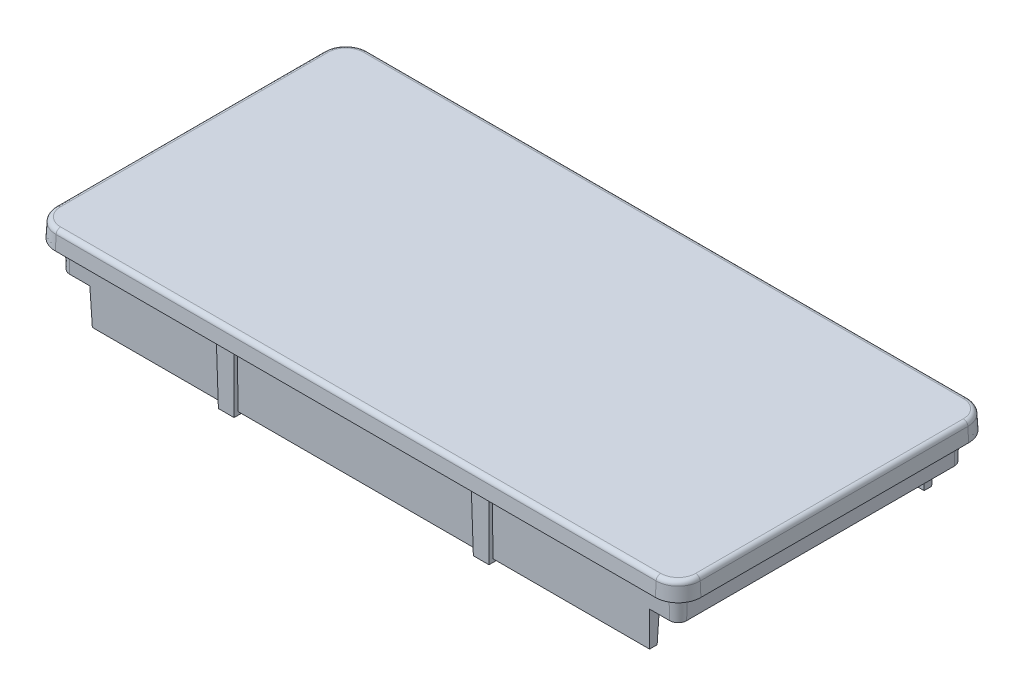
SolidWorks part; units mm, degrees
material "ABS PC"
ref_plane "Front" through (0, 0, 0) normal (0, 0, 1) x (1, 0, 0)
ref_plane "Top" through (0, 0, 0) normal (0, 1, 0) x (1, 0, 0)
ref_plane "Right" through (0, 0, 0) normal (1, 0, 0) x (0, 0, -1)
sketch "Sketch1" plane through (0, 0, 0) normal (0, 1, 0) x (1, 0, 0)
  line L1 (-32.95, -17.2) -> (32.95, -17.2)
  line L2 (-35.45, -14.7) -> (-35.45, 14.7)
  line L3 (-32.95, 17.2) -> (32.95, 17.2)
  line L4 (35.45, -14.7) -> (35.45, 14.7)
  line L5 (-35.45, -17.2) -> (35.45, 17.2) construction
  line L6 (-35.45, 17.2) -> (35.45, -17.2) construction
  arc A0 (32.95, -17.2) -> (35.45, -14.7) centre (32.95, -14.7) ccw
  arc A1 (-35.45, 14.7) -> (-32.95, 17.2) centre (-32.95, 14.7) cw
  arc A2 (-32.95, -17.2) -> (-35.45, -14.7) centre (-32.95, -14.7) cw
  arc A3 (32.95, 17.2) -> (35.45, 14.7) centre (32.95, 14.7) cw
  point P0 (0, 0)
  dimension "D3" = 2.5
  dimension "D1" = 70.9
  dimension "D2" = 34.4
extrude "Boss-Extrude1" add sketch "Sketch1" along normal blind 2 draft 3
fillet "Fillet1" radius 0.5 8 edges at (0, 2, 17.0952) (-34.6437, 2, 16.3937) (-35.3452, 2, 0) (-34.6437, 2, -16.3937) (0, 2, -17.0952) (34.6437, 2, -16.3937) (35.3452, 2, 0) (34.6437, 2, 16.3937)
sketch "Sketch2" plane through (0, 0, 0) normal (0, -1, 0) x (1, 0, 0)
  line L8 (32.95, 16.45) -> (-32.95, 16.45)
  line L9 (-34.7, 14.7) -> (-34.7, -14.7)
  line L10 (-32.95, -16.45) -> (32.95, -16.45)
  line L11 (34.7, -14.7) -> (34.7, 14.7)
  line L12 (32.95, 16.45) -> (-32.95, 16.45)
  line L13 (-34.7, 14.7) -> (-34.7, -14.7)
  line L14 (-32.95, -16.45) -> (32.95, -16.45)
  line L15 (34.7, -14.7) -> (34.7, 14.7)
  arc A8 (34.7, 14.7) -> (32.95, 16.45) centre (32.95, 14.7) ccw
  arc A9 (-32.95, 16.45) -> (-34.7, 14.7) centre (-32.95, 14.7) ccw
  arc A10 (-34.7, -14.7) -> (-32.95, -16.45) centre (-32.95, -14.7) ccw
  arc A11 (32.95, -16.45) -> (34.7, -14.7) centre (32.95, -14.7) ccw
  arc A12 (34.7, 14.7) -> (32.95, 16.45) centre (32.95, 14.7) ccw
  arc A13 (-32.95, 16.45) -> (-34.7, 14.7) centre (-32.95, 14.7) ccw
  arc A14 (-34.7, -14.7) -> (-32.95, -16.45) centre (-32.95, -14.7) ccw
  arc A15 (32.95, -16.45) -> (34.7, -14.7) centre (32.95, -14.7) ccw
  dimension "D1" = 0.75
extrude "Cut-Extrude1" cut sketch "Sketch2" against normal blind 0.5
sketch "Sketch4" plane through (0, 0.5, 0) normal (0, -1, 0) x (1, 0, 0)
  line L1 (31.65, -14.4) -> (-31.65, -14.4)
  line L2 (32.65, -13.4) -> (32.65, 13.4)
  line L3 (31.65, 14.4) -> (-31.65, 14.4)
  line L4 (-32.65, -13.4) -> (-32.65, 13.4)
  line L5 (32.65, -14.4) -> (-32.65, 14.4) construction
  line L6 (32.65, 14.4) -> (-32.65, -14.4) construction
  line L8 (32.95, 15.75) -> (-32.95, 15.75)
  line L9 (-34, 14.7) -> (-34, -14.7)
  line L10 (-32.95, -15.75) -> (32.95, -15.75)
  line L11 (34, -14.7) -> (34, 14.7)
  line L12 (32.95, 15.75) -> (-32.95, 15.75)
  line L13 (-34, 14.7) -> (-34, -14.7)
  line L14 (-32.95, -15.75) -> (32.95, -15.75)
  line L15 (34, -14.7) -> (34, 14.7)
  arc A0 (32.65, 13.4) -> (31.65, 14.4) centre (31.65, 13.4) ccw
  arc A1 (31.65, -14.4) -> (32.65, -13.4) centre (31.65, -13.4) ccw
  arc A2 (-31.65, -14.4) -> (-32.65, -13.4) centre (-31.65, -13.4) cw
  arc A3 (-31.65, 14.4) -> (-32.65, 13.4) centre (-31.65, 13.4) ccw
  arc A8 (34, 14.7) -> (32.95, 15.75) centre (32.95, 14.7) ccw
  arc A9 (-32.95, 15.75) -> (-34, 14.7) centre (-32.95, 14.7) ccw
  arc A10 (-34, -14.7) -> (-32.95, -15.75) centre (-32.95, -14.7) ccw
  arc A11 (32.95, -15.75) -> (34, -14.7) centre (32.95, -14.7) ccw
  arc A12 (34, 14.7) -> (32.95, 15.75) centre (32.95, 14.7) ccw
  arc A13 (-32.95, 15.75) -> (-34, 14.7) centre (-32.95, 14.7) ccw
  arc A14 (-34, -14.7) -> (-32.95, -15.75) centre (-32.95, -14.7) ccw
  arc A15 (32.95, -15.75) -> (34, -14.7) centre (32.95, -14.7) ccw
  point P0 (0, 0)
  dimension "D4" = 1
  dimension "D2" = 1.35
  dimension "D3" = 1.35
  dimension "D1" = 0.7
extrude "Boss-Extrude2" add sketch "Sketch4" along normal offset from surface 8.95 draft 2
sketch "Sketch5" plane through (0, 0.5, 0) normal (0, -1, 0) x (1, 0, 0)
  line L4 (31.65, 14.4) -> (-31.65, 14.4)
  line L5 (-32.65, 13.4) -> (-32.65, -13.4)
  line L6 (-31.65, -14.4) -> (31.65, -14.4)
  line L7 (32.65, -13.4) -> (32.65, 13.4)
  line L8 (31.65, 14.4) -> (-31.65, 14.4)
  line L9 (-32.65, 13.4) -> (-32.65, -13.4)
  line L10 (-31.65, -14.4) -> (31.65, -14.4)
  line L11 (32.65, -13.4) -> (32.65, 13.4)
  arc A4 (-31.65, 14.4) -> (-32.65, 13.4) centre (-31.65, 13.4) ccw
  arc A5 (-32.65, -13.4) -> (-31.65, -14.4) centre (-31.65, -13.4) ccw
  arc A6 (31.65, -14.4) -> (32.65, -13.4) centre (31.65, -13.4) ccw
  arc A7 (32.65, 13.4) -> (31.65, 14.4) centre (31.65, 13.4) ccw
  arc A8 (-31.65, 14.4) -> (-32.65, 13.4) centre (-31.65, 13.4) ccw
  arc A9 (-32.65, -13.4) -> (-31.65, -14.4) centre (-31.65, -13.4) ccw
  arc A10 (31.65, -14.4) -> (32.65, -13.4) centre (31.65, -13.4) ccw
  arc A11 (32.65, 13.4) -> (31.65, 14.4) centre (31.65, 13.4) ccw
  dimension "D1" = 0
extrude "Cut-Extrude2" cut sketch "Sketch5" against normal blind 0.2 draft 2
sketch "Sketch7" plane through (0, -6.95, 0) normal (0, -1, 0) x (1, 0, 0)
  line L1 (40, -13.25) -> (-40, -13.25)
  line L2 (40, -13.25) -> (40, 13.25)
  line L3 (40, 13.25) -> (-40, 13.25)
  line L4 (-40, -13.25) -> (-40, 13.25)
  line L5 (40, -13.25) -> (-40, 13.25) construction
  line L6 (40, 13.25) -> (-40, -13.25) construction
  point P0 (0, 0)
  dimension "D1" = 26.5
  dimension "D2" = 80
extrude "Cut-Extrude3" cut sketch "Sketch7" against normal offset from surface (3.95 mm away) 5 up to face at (0, 2, 0)
sketch "Sketch6" plane through (0, -6.95, 0) normal (0, -1, 0) x (1, 0, 0)
  line L0 (0, 25.2339) -> (0, -25.4955) construction
  line L1 (-36.417, 18.167) -> (-30.6, 18.167)
  line L2 (-36.417, 18.167) -> (-36.417, 12.35)
  line L3 (-36.417, 12.35) -> (-30.6, 12.35)
  line L4 (-30.6, 18.167) -> (-30.6, 12.35)
  line L5 (-36.417, 18.167) -> (-30.6, 12.35) construction
  line L6 (-36.417, 12.35) -> (-30.6, 18.167) construction
  line L7 (-41.5983, 0) -> (43.5606, 0) construction
  line L8 (36.417, 12.35) -> (30.6, 18.167) construction
  line L9 (36.417, 18.167) -> (30.6, 12.35) construction
  line L10 (30.6, 18.167) -> (30.6, 12.35)
  line L11 (36.417, 12.35) -> (30.6, 12.35)
  line L12 (36.417, 18.167) -> (36.417, 12.35)
  line L13 (36.417, 18.167) -> (30.6, 18.167)
  line L14 (36.417, -18.167) -> (30.6, -12.35) construction
  line L15 (36.417, -12.35) -> (30.6, -18.167) construction
  line L16 (-36.417, -12.35) -> (-30.6, -18.167) construction
  line L17 (-36.417, -18.167) -> (-30.6, -12.35) construction
  line L18 (36.417, -18.167) -> (30.6, -18.167)
  line L19 (36.417, -18.167) -> (36.417, -12.35)
  line L20 (36.417, -12.35) -> (30.6, -12.35)
  line L21 (30.6, -18.167) -> (30.6, -12.35)
  line L22 (-30.6, -18.167) -> (-30.6, -12.35)
  line L23 (-36.417, -12.35) -> (-30.6, -12.35)
  line L24 (-36.417, -18.167) -> (-36.417, -12.35)
  line L25 (-36.417, -18.167) -> (-30.6, -18.167)
  arc A0 (-32.95, 15.4898) -> (-33.7398, 14.7) centre (-32.95, 14.7) ccw construction
  point P0 (-33.5085, 15.2585)
  point P14 (33.5085, 15.2585)
  point P23 (33.5085, -15.2585)
  point P24 (-33.5085, -15.2585)
  dimension "D1" = 61.2
extrude "Cut-Extrude4" cut sketch "Sketch6" against normal offset from surface 5 draft 2
fillet "Fillet3" radius 0.5 8 edges at (32.3522, 0.7, 14.1022) (32.643, 0.7, 0) (32.3522, 0.7, -14.1022) (0, 0.7, -14.393) (-32.3522, 0.7, -14.1022) (-32.643, 0.7, 0) (-32.3522, 0.7, 14.1022) (0, 0.7, 14.393)
sketch "Sketch16" plane through (0, 0.7, 0) normal (0, -1, 0) x (1, 0, 0)
  line L0 (-35.45, -14.7) -> (-35.45, 14.7) construction
  line L1 (-16.45, 14.075) -> (-14.45, 14.075)
  line L2 (-16.45, 14.075) -> (-16.45, 16.075)
  line L3 (-16.45, 16.075) -> (-14.45, 16.075)
  line L4 (-14.45, 14.075) -> (-14.45, 16.075)
  line L5 (-7.0762, 15.075) -> (-30.6, 15.075) construction
  line L6 (-30.6, 14.6602) -> (-30.6, 15.4898) construction
  line L7 (-16.45, 14.075) -> (-14.45, 16.075) construction
  line L8 (-16.45, 16.075) -> (-14.45, 14.075) construction
  line L9 (11.55, 14.075) -> (13.55, 14.075)
  line L10 (11.55, 14.075) -> (11.55, 16.075)
  line L11 (32.1602, 0) -> (-39.5501, 0) construction
  line L12 (32.1602, -13.4) -> (32.1602, 13.4) construction
  line L13 (11.55, 16.075) -> (13.55, 16.075)
  line L14 (13.55, 14.075) -> (13.55, 16.075)
  line L15 (11.55, 14.075) -> (13.55, 16.075) construction
  line L16 (11.55, 16.075) -> (13.55, 14.075) construction
  line L17 (11.55, -16.075) -> (13.55, -14.075) construction
  line L18 (11.55, -14.075) -> (13.55, -16.075) construction
  line L19 (-16.45, -16.075) -> (-14.45, -14.075) construction
  line L20 (-16.45, -14.075) -> (-14.45, -16.075) construction
  line L21 (13.55, -14.075) -> (13.55, -16.075)
  line L22 (11.55, -16.075) -> (13.55, -16.075)
  line L23 (11.55, -14.075) -> (11.55, -16.075)
  line L24 (11.55, -14.075) -> (13.55, -14.075)
  line L25 (-14.45, -14.075) -> (-14.45, -16.075)
  line L26 (-16.45, -16.075) -> (-14.45, -16.075)
  line L27 (-16.45, -14.075) -> (-16.45, -16.075)
  line L28 (-16.45, -14.075) -> (-14.45, -14.075)
  point P0 (-15.45, 15.075)
  point P15 (12.55, 15.075)
  point P28 (12.55, -15.075)
  point P29 (-15.45, -15.075)
  dimension "D1" = 2
  dimension "D2" = 19
extrude "Boss-Extrude7" add sketch "Sketch16" along normal blind 8 draft 1
sketch "Sketch17" plane through (0, 0.7, 0) normal (0, -1, 0) x (1, 0, 0)
  line L0 (33.325, 12.2152) -> (33.325, -12.2152) construction
  line L1 (33.325, -1) -> (34.325, -1)
  line L2 (33.325, -1) -> (33.325, 1)
  line L3 (33.325, 1) -> (34.325, 1)
  line L4 (34.325, -1) -> (34.325, 1)
  line L7 (-33.325, 12.2152) -> (-33.325, -12.2152) construction
  line L10 (33.325, 0) -> (32.7722, 0) construction
  line L11 (32.7722, 13.4) -> (32.7722, -13.4) construction
  line L12 (-32.95, 17.2) -> (32.95, 17.2) construction
  line L13 (-33.325, 9.2) -> (-34.325, 9.2)
  line L14 (-33.325, 9.2) -> (-33.325, 7.2)
  line L15 (-33.325, 7.2) -> (-34.325, 7.2)
  line L16 (-34.325, 9.2) -> (-34.325, 7.2)
  line L17 (-33.325, -4.8) -> (-34.325, -4.8)
  line L18 (-33.325, -4.8) -> (-33.325, -6.8)
  line L19 (-33.325, -6.8) -> (-34.325, -6.8)
  line L20 (-34.325, -4.8) -> (-34.325, -6.8)
  dimension "D1" = 1
  dimension "D2" = 2
  dimension "D3" = 8
  dimension "D4" = 2
extrude "Boss-Extrude8" [suppressed] add sketch "Sketch17" along normal blind 4 draft 1
chamfer "Chamfer1" [suppressed] distance 1.75 distance2 0.45
